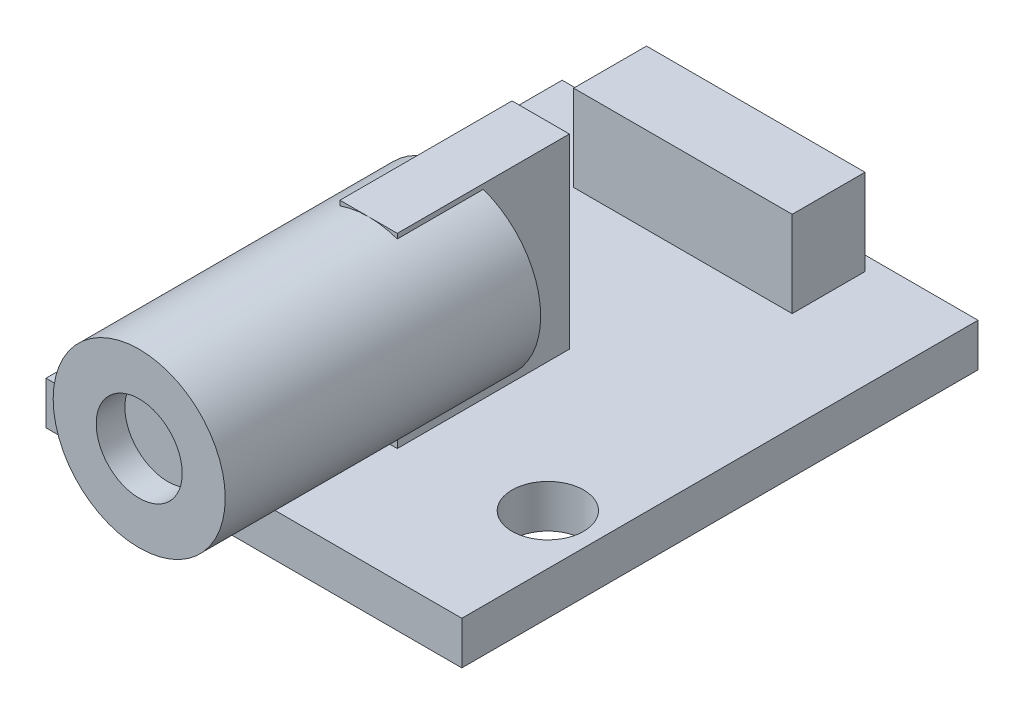
SolidWorks part; units mm, degrees
ref_plane "Front" through (0, 0, 0) normal (0, 0, 1) x (1, 0, 0)
ref_plane "Top" through (0, 0, 0) normal (0, 1, 0) x (1, 0, 0)
ref_plane "Right" through (0, 0, 0) normal (1, 0, 0) x (0, 0, -1)
sketch "Sketch1" plane through (0, 0, 0) normal (0, 1, 0) x (1, 0, 0)
  line L1 (-7.25, 9) -> (7.25, 9)
  line L2 (-7.25, 9) -> (-7.25, -9)
  line L3 (-7.25, -9) -> (7.25, -9)
  line L4 (7.25, 9) -> (7.25, -9)
  line L5 (-7.25, 9) -> (7.25, -9) construction
  line L6 (-7.25, -9) -> (7.25, 9) construction
  point P0 (0, 0)
  dimension "D1" = 14.5
  dimension "D2" = 18
extrude "Boss-Extrude1" add sketch "Sketch1" along normal blind 1.5
sketch "Sketch2" plane through (0, 0, 9) normal (0, 0, 1) x (1, 0, 0)
  line L0 (-7.25, 1.5) -> (7.25, 1.5) construction
  circle A0 centre (0, 5) radius 3
  dimension "D1" = 6
  dimension "D2" = 0.5
extrude "Boss-Extrude2" add sketch "Sketch2" along normal blind 4 and the other way blind 7 separate body
sketch "Sketch3" plane through (0, 0, 13) normal (0, 0, 1) x (1, 0, 0)
  circle A0 centre (0, 5) radius 1.5
  dimension "D1" = 3
extrude "Cut-Extrude1" cut sketch "Sketch3" against normal blind 1
sketch "Sketch4" plane through (0, 1.5, 0) normal (0, 1, 0) x (1, 0, 0)
  line L0 (3, -2) -> (-3, -2) construction
  line L1 (-1, 1) -> (1, 1)
  line L2 (-1, 1) -> (-1, -5)
  line L3 (-1, -5) -> (1, -5)
  line L4 (1, 1) -> (1, -5)
  line L5 (-1, 1) -> (1, -5) construction
  line L6 (-1, -5) -> (1, 1) construction
  point P0 (0, -2)
  dimension "D1" = 6
  dimension "D2" = 2
extrude "Boss-Extrude3" add sketch "Sketch4" along normal blind 6.5
sketch "Sketch5" plane through (0, 1.5, 0) normal (0, 1, 0) x (1, 0, 0)
  line L0 (7.25, 9) -> (-7.25, 9) construction
  line L1 (-3.81, 8.5) -> (3.81, 8.5)
  line L2 (-3.81, 8.5) -> (-3.81, 5.96)
  line L3 (-3.81, 5.96) -> (3.81, 5.96)
  line L4 (3.81, 8.5) -> (3.81, 5.96)
  line L5 (-3.81, 8.5) -> (3.81, 5.96) construction
  line L6 (-3.81, 5.96) -> (3.81, 8.5) construction
  point P0 (0, 7.23)
  dimension "D1" = 7.62
  dimension "D2" = 2.54
  dimension "D3" = 0.5
extrude "Boss-Extrude4" add sketch "Sketch5" along normal blind 3
sketch "Sketch6" plane through (0, 0, 0) normal (1, 0, 0) x (0, 0, -1)
  line L0 (6.98, 4.5) -> (6.98, 5)
  line L1 (5.96, 4.5) -> (8.5, 4.5) construction
  line L2 (8.48, 6.5) -> (15.23, 6.5)
  line L3 (15.23, 6.5) -> (15.23, 6)
  line L4 (15.23, 6) -> (8.48, 6)
  line L5 (7.48, 5) -> (7.48, 4.5)
  line L6 (7.48, 4.5) -> (6.98, 4.5)
  line L7 (7.23, 1.5) -> (7.23, 4.5) construction
  line L8 (5.96, 1.5) -> (8.5, 1.5) construction
  arc A0 (6.98, 5) -> (8.48, 6.5) centre (8.48, 5) cw
  arc A1 (8.48, 6) -> (7.48, 5) centre (8.48, 5) ccw
  dimension "D1" = 0.5
  dimension "D4" = 1.5
  dimension "D2" = 2
  dimension "D3" = 8
extrude "Boss-Extrude5" [suppressed] add sketch "Sketch6" along normal mid plane 0.5
pattern_linear "LPattern1" [suppressed] count 2 spacing 2.54 count 2 spacing 2.54
sketch "Sketch7" plane through (0, 1.5, 0) normal (0, 1, 0) x (1, 0, 0)
  line L0 (0, 0) -> (0, -13) construction
  line L1 (-3, -13) -> (3, -13) construction
  line L2 (-7.25, 9) -> (-7.25, -9) construction
  line L3 (-7.25, -9) -> (7.25, -9) construction
  circle A0 centre (-5.5, -4.25) radius 1.25
  circle A1 centre (5.5, -4.25) radius 1.25
  dimension "D1" = 2.5
  dimension "D2" = 0.5
  dimension "D3" = 3.5
extrude "Cut-Extrude2" cut sketch "Sketch7" against normal through all
